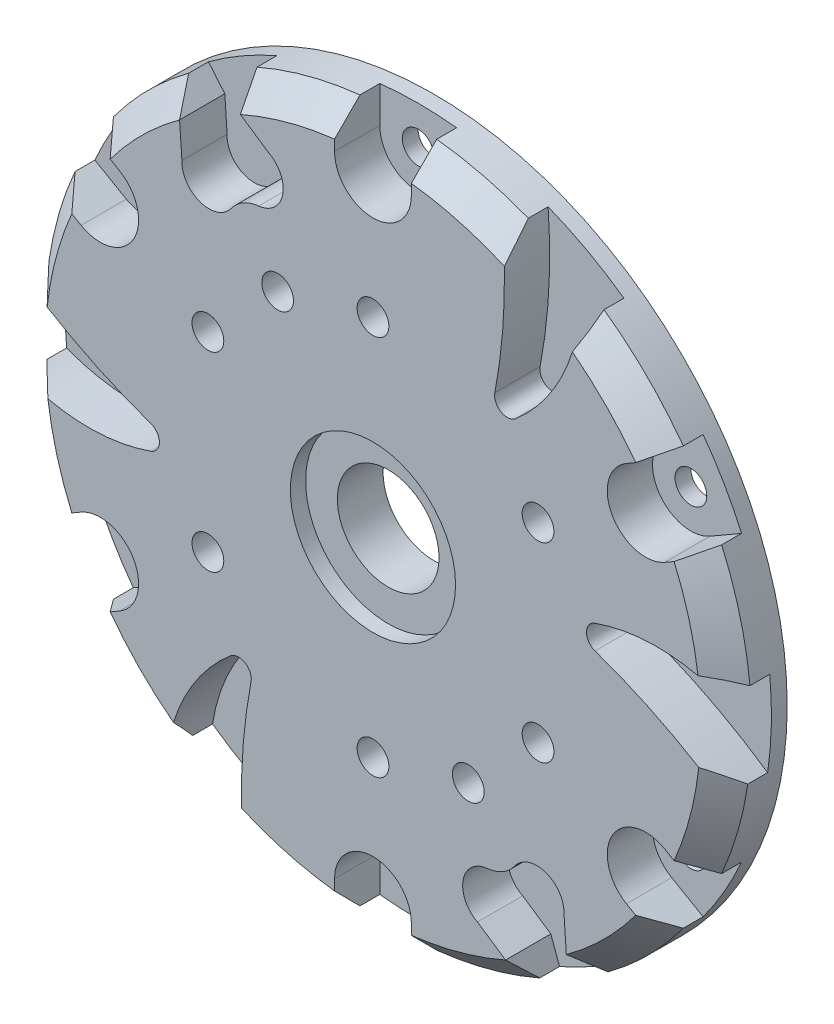
SolidWorks part; units mm, degrees
ref_plane "Front Plane" through (0, 0, 0) normal (0, 0, 1) x (1, 0, 0)
ref_plane "Top Plane" through (0, 0, 0) normal (0, 1, 0) x (1, 0, 0)
ref_plane "Right Plane" through (0, 0, 0) normal (1, 0, 0) x (0, 0, -1)
sketch "Sketch1" plane through (0, 0, 0) normal (0, 0, 1) x (1, 0, 0)
  circle A0 centre (0, 0) radius 27.8
  dimension "D1" = 55.6
extrude "Boss-Extrude1" add sketch "Sketch1" along normal blind 4.8
chamfer "Chamfer1" distance 2 angle 45 1 edges at (27.8, 0, 4.8)
sketch "Sketch2" plane through (0, 0, 4.8) normal (0, 0, 1) x (1, 0, 0)
  line L0 (0, 0) -> (0, 27.8) construction
  line L1 (-3.02, 24.78) -> (-3.02, 27.6355)
  line L2 (3.02, 24.78) -> (3.02, 27.6355)
  line L3 (19.9501, 15.0054) -> (22.423, 16.4331)
  line L4 (22.9701, 9.7746) -> (25.443, 11.2023)
  line L5 (0, 0) -> (24.0755, 13.9) construction
  line L6 (22.9701, -9.7746) -> (25.443, -11.2023)
  line L7 (19.9501, -15.0054) -> (22.423, -16.4331)
  line L8 (0, 0) -> (24.0755, -13.9) construction
  line L9 (3.02, -24.78) -> (3.02, -27.6355)
  line L10 (-3.02, -24.78) -> (-3.02, -27.6355)
  line L11 (0, 0) -> (0, -27.8) construction
  line L12 (-19.9501, -15.0054) -> (-22.423, -16.4331)
  line L13 (-22.9701, -9.7746) -> (-25.443, -11.2023)
  line L14 (0, 0) -> (-24.0755, -13.9) construction
  line L15 (-22.9701, 9.7746) -> (-25.443, 11.2023)
  line L16 (-19.9501, 15.0054) -> (-22.423, 16.4331)
  line L17 (0, 0) -> (-24.0755, 13.9) construction
  line L20 (0, 0) -> (-12.9, 22.3435) construction
  line L21 (-9.1968, 20.2054) -> (-7.9168, 17.9884) construction
  line L22 (-12.9, 18.0674) -> (-11.62, 15.8503) construction
  line L23 (-8.2184, 22.1064) -> (-10.4348, 23.5957)
  line L24 (-10.4348, 23.5957) -> (-11.3266, 26.0379)
  line L25 (-15.2171, 20.8346) -> (-16.8862, 22.8281)
  line L26 (-15.0356, 18.1705) -> (-15.2171, 20.8346)
  line L27 (8.2184, -22.1064) -> (10.4348, -23.5957)
  line L28 (15.0356, -18.1705) -> (15.2171, -20.8346)
  line L29 (15.2171, -20.8346) -> (16.8862, -22.8281)
  line L30 (10.4348, -23.5957) -> (11.3266, -26.0379)
  line L31 (3, -5.1962) -> (-21.0755, -19.0962) construction
  line L32 (3, -5.1962) -> (27.0755, 8.7038) construction
  line L33 (-3, 5.1962) -> (-27.0755, -8.7038) construction
  line L34 (-3, 5.1962) -> (21.0755, 19.0962) construction
  arc A0 (-3.02, 24.78) -> (3.02, 24.78) centre (0, 24.78) ccw
  circle A1 centre (0, 0) radius 27.8 construction
  arc A2 (19.9501, 15.0054) -> (22.9701, 9.7746) centre (21.4601, 12.39) ccw
  arc A3 (22.9701, -9.7746) -> (19.9501, -15.0054) centre (21.4601, -12.39) ccw
  arc A4 (3.02, -24.78) -> (-3.02, -24.78) centre (0, -24.78) ccw
  arc A5 (-19.9501, -15.0054) -> (-22.9701, -9.7746) centre (-21.4601, -12.39) ccw
  arc A6 (-22.9701, 9.7746) -> (-19.9501, 15.0054) centre (-21.4601, 12.39) ccw
  arc A7 (-11.0484, 19.1364) -> (-11.1022, 19.2245) centre (-12.9, 18.0674) ccw
  arc A8 (-8.9908, 18.0773) -> (-8.2184, 22.1064) centre (-9.1968, 20.2054) ccw
  circle A9 centre (0, 0) radius 25.8 construction
  circle A10 centre (0, 0) radius 22.2 construction
  arc A11 (-11.16, 16.8249) -> (-8.9908, 18.0773) centre (-8.6994, 15.0678) cw
  circle A12 centre (0, 0) radius 28.3948 construction
  arc A13 (-15.0356, 18.1705) -> (-11.16, 16.8249) centre (-12.9, 18.0674) ccw
  arc A14 (-11.0978, 19.227) -> (-11.0484, 19.1364) centre (-9.1968, 20.2054) ccw
  arc A16 (8.2184, -22.1064) -> (8.9908, -18.0773) centre (9.1968, -20.2054) cw
  arc A17 (8.9908, -18.0773) -> (11.16, -16.8249) centre (8.6994, -15.0678) ccw
  arc A18 (11.16, -16.8249) -> (15.0356, -18.1705) centre (12.9, -18.0674) cw
  arc A19 (11.3266, -26.0379) -> (16.8862, -22.8281) centre (0, 0) ccw
  arc A20 (-22.423, 16.4331) -> (-25.443, 11.2023) centre (0, 0) ccw
  arc A21 (3.02, 27.6355) -> (-3.02, 27.6355) centre (0, 0) ccw
  arc A22 (25.443, 11.2023) -> (22.423, 16.4331) centre (0, 0) ccw
  arc A23 (22.423, -16.4331) -> (25.443, -11.2023) centre (0, 0) ccw
  arc A24 (-3.02, -27.6355) -> (3.02, -27.6355) centre (0, 0) ccw
  arc A25 (-25.443, -11.2023) -> (-22.423, -16.4331) centre (0, 0) ccw
  arc A26 (11.2246, 13.6916) -> (16.2719, 23.27) centre (1.7214, 24.8184) ccw
  circle A27 centre (0, 0) radius 15 construction
  arc A28 (9.5929, 14.6399) -> (10.1684, 26.5117) centre (-32.0867, 22.6102) ccw
  arc A29 (11.2246, 13.6916) -> (9.5929, 14.6399) centre (10.5751, 14.4521) cw
  arc A30 (17.4696, 2.8749) -> (28.2883, 2.4569) centre (22.3541, -10.9184) cw
  arc A31 (17.4696, 2.8749) -> (17.475, 0.9878) centre (17.8034, 1.9323) ccw
  arc A32 (17.475, 0.9878) -> (28.044, -4.4497) centre (3.5377, -39.093) cw
  arc A33 (-17.4696, -2.8749) -> (-28.2883, -2.4569) centre (-22.3541, 10.9184) cw
  arc A34 (-9.5929, -14.6399) -> (-10.1684, -26.5117) centre (32.0867, -22.6102) ccw
  arc A35 (-11.2246, -13.6916) -> (-9.5929, -14.6399) centre (-10.5751, -14.4521) cw
  arc A36 (-11.2246, -13.6916) -> (-16.2719, -23.27) centre (-1.7214, -24.8184) ccw
  arc A37 (-17.4696, -2.8749) -> (-17.475, -0.9878) centre (-17.8034, -1.9323) ccw
  arc A38 (-17.475, -0.9878) -> (-28.044, 4.4497) centre (-3.5377, 39.093) cw
  arc A39 (-11.3266, 26.0379) -> (-16.8862, 22.8281) centre (0, 0) ccw
  arc A40 (16.2719, 23.27) -> (10.1684, 26.5117) centre (0, 0) ccw
  arc A41 (28.044, -4.4497) -> (21.0354, 19.073) centre (0, 0) ccw
  arc A42 (-16.2719, -23.27) -> (-10.1684, -26.5117) centre (0, 0) ccw
  arc A43 (-28.044, 4.4497) -> (-21.0354, -19.073) centre (0, 0) ccw
  point P88 (9.0378, 12.1462)
  point P91 (9.0378, 12.1462)
  dimension "D1" = 6.04
  dimension "D4" = 30
  dimension "D5" = 44.4
  dimension "D6" = 2.138
  dimension "D7" = 3.0236
  dimension "D11" = 30
  dimension "D12" = 1
  dimension "D8" = 5.5221
  dimension "D9" = 6.4197
  dimension "D10" = 7.8718
extrude "Cut-Extrude1" cut sketch "Sketch2" against normal blind 3.56
hole_wizard "M3x0.5 Tapped Hole1" positions "Sketch6" profile "Sketch3" tap size "M3x0.5" standard "ANSI Metric"
sketch "Sketch6" plane through (0, 0, 4.8) normal (0, 0, 1) x (1, 0, 0)
  line L0 (0.001, 0) -> (0, 15) construction
  line L1 (0.001, 0) -> (7.5001, 12.9909) construction
  circle A0 centre (0, 0) radius 15 construction
  point P0 (0, 15)
  point P26 (7.5001, 12.9909) [skipped]
  point P27 (12.9909, 7.5009)
  point P28 (15.001, 0.001) [skipped]
  point P29 (12.9919, -7.4991)
  point P30 (7.5019, -12.9899)
  point P31 (0.002, -15)
  point P32 (-7.4981, -12.9909) [skipped]
  point P33 (-12.9889, -7.5009)
  point P34 (-14.999, -0.001) [skipped]
  point P35 (-12.9899, 7.4991)
  point P36 (-7.4999, 12.9899)
  dimension "D1" = 30
  dimension "D3" = 30
  dimension "D2" = 12
sketch "Sketch3" plane through (0, 15, 4.8) normal (1, 0, 0) x (0, -1, 0)
  line L0 (0, 0) -> (0, 4.8)
  line L1 (0, 4.8) -> (1.25, 4.8)
  line L2 (1.25, 4.8) -> (1.25, 0)
  line L5 (1.25, 0) -> (0, 0)
  line L11 (0, -6.35) -> (0, 107.95) construction
  dimension "Thru Tap Drill Dia." = 2.5
  dimension "Thru Tap Drill Depth" = 4.8
cosmetic thread "Hole Thread1" parameters "D2"=3
cosmetic thread "Hole Thread2" parameters "D2"=3
cosmetic thread "Hole Thread3" parameters "D2"=3
cosmetic thread "Hole Thread4" parameters "D2"=3
cosmetic thread "Hole Thread5" parameters "D2"=3
cosmetic thread "Hole Thread6" parameters "D2"=3
cosmetic thread "Hole Thread7" parameters "D2"=3
cosmetic thread "Hole Thread8" parameters "D2"=3
sketch "Sketch7" plane through (0, 0, 4.8) normal (0, 0, 1) x (1, 0, 0)
  circle A0 centre (0, 0) radius 4
  dimension "D1" = 8
extrude "Cut-Extrude2" cut sketch "Sketch7" against normal through all
sketch "Sketch8" plane through (0, 0, 4.8) normal (0, 0, 1) x (1, 0, 0)
  circle A0 centre (0, 0) radius 6.5
  dimension "D1" = 13
extrude "Cut-Extrude3" cut sketch "Sketch8" against normal blind 1.2
hole_wizard "M3x0.5 Tapped Hole2" positions "Sketch10" profile "Sketch9" tap size "M3x0.5" standard "ANSI Metric" end condition through all
sketch "Sketch10" plane through (0, 0, 4.8) normal (0, 0, 1) x (1, 0, 0)
  arc A0 (-3.02, 24.78) -> (3.02, 24.78) centre (0, 24.78) ccw construction
  point P0 (0, 24.78)
  point P12 (21.4601, 12.39)
  point P13 (21.4601, -12.39)
  point P14 (0, -24.78)
  point P15 (-21.4601, -12.39)
  point P16 (-21.4601, 12.39)
  point P17 (0, 0)
  dimension "D1" = 0
  dimension "D2" = 6
sketch "Sketch9" plane through (0, 24.78, 4.8) normal (1, 0, 0) x (0, -1, 0)
  line L0 (0, 0) -> (0, 4.8)
  line L1 (0, 4.8) -> (1.25, 4.8)
  line L2 (1.25, 4.8) -> (1.25, 0)
  line L5 (1.25, 0) -> (0, 0)
  line L11 (0, -6.35) -> (0, 107.95) construction
  dimension "Thru Tap Drill Dia." = 2.5
  dimension "Thru Tap Drill Depth" = 4.8
cosmetic thread "Hole Thread9" parameters "D2"=3
cosmetic thread "Hole Thread10" parameters "D2"=3
cosmetic thread "Hole Thread11" parameters "D2"=3
cosmetic thread "Hole Thread12" parameters "D2"=3
cosmetic thread "Hole Thread13" parameters "D2"=3
cosmetic thread "Hole Thread14" parameters "D2"=3
